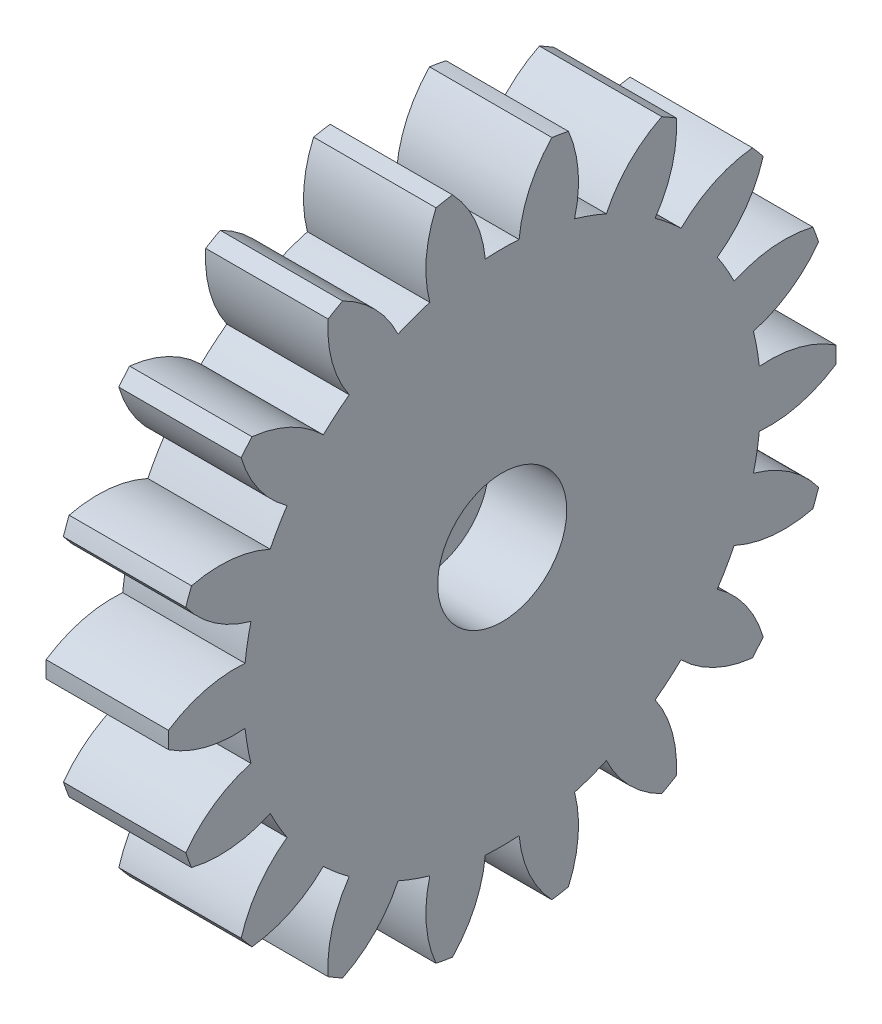
SolidWorks part; units mm, degrees
ref_plane "Plane1" through (0, 0, 0) normal (0, 0, 1) x (1, 0, 0)
ref_plane "Plane2" through (0, 0, 0) normal (0, 1, 0) x (1, 0, 0)
ref_plane "Plane3" through (0, 0, 0) normal (1, 0, 0) x (0, 0, -1)
sketch "HoldingSke" plane through (0, 0, 0) normal (0, 1, 0) x (1, 0, 0)
  line L0 (0, 0) -> (0.634, -0.206)
  line L1 (-15, 0) -> (100, 0) construction
  line L2 (0, 0) -> (-2.1039, 2.3779)
  line L3 (0, 0) -> (-11.863, 4.5341)
  line L4 (0, 0) -> (8.2133, 2.6687)
  line L5 (0, 0) -> (-46.8476, -17.4728)
  line L6 (0, 0) -> (-5.8027, -3.9151)
  line L7 (-2.1039, 2.3779) -> (8.6586, 51.2059)
  line L8 (-76.2, 54.61) -> (-75.3, 54.61)
  line L9 (-71.009, 38.7566) -> (-53.1078, 45.2721)
  line L10 (-76.2, 71.12) -> (104.1128, 71.12)
  line L11 (0, 0) -> (-7, 0)
  line L12 (-76.2, 101.6) -> (-76.147, 101.6)
  line L13 (24.9733, 27.94) -> (52.9518, 28.4284)
  line L14 (24.9733, 27.94) -> (24.9743, 27.94)
  line L15 (24.9733, 27.94) -> (100.4006, 29.5858)
  line L16 (-63.627, -1.5) -> (-12.827, -1.5)
  circle A0 centre (0, 0) radius 2.5
  circle A1 centre (0, 0) radius 11.624
  circle A2 centre (0, 0) radius 37.5
  circle A3 centre (0, 0) radius 2.5
  dimension "MHD" = 23.248
  dimension "Hub_dia" = 75
  dimension "Bore" = 5
  dimension "MBD" = 5
  dimension "Num_teeth" = 18
  dimension "Pitch" = 0.6667
  dimension "Overall_len" = 50
  dimension "Show_teeth" = 18
  dimension "Thickness" = 7
  dimension "OAL" = 50.0001
  dimension "T_dim" = 0.9
  dimension "Ap" = 20
  dimension "H" = 19.05
  dimension "Pitch_radius" = 180.3128
  dimension "Width" = 7
  dimension "Backlash" = 0.053
  dimension "Addendum_fac" = 1
  dimension "Dedendum_fac" = 1.25
  dimension "Clearance_fac" = 0.25
  dimension "Dedendum_add" = 0.001
  dimension "Module" = 1.5
sketch "BasProSke" plane through (0, 0, 0) normal (0, 1, 0) x (1, 0, 0)
  line L0 (-10, 0) -> (60, 0) construction
  line L1 (0, 0) -> (0, 15)
  line L2 (0, 0) -> (7, 0)
  line L3 (7, 0) -> (7, 15)
  line L4 (7, 15) -> (0, 15)
  dimension "Thickness" = 7
  dimension "Diameter" = 30
revolve "Base-Revolve" add sketch "BasProSke" angle 360 about L0
sketch "TooCutSke" plane through (0, 0, 0) normal (1, 0, 0) x (0, 0, -1)
  line L1 (0, 0) -> (0, 107) construction
  line L2 (0, 0) -> (-1.2693, 13.4402) construction
  line L3 (0, 0) -> (-4.6734, 26.504) construction
  line L4 (-1.2693, 13.4402) -> (-2.3367, 13.252) construction
  arc A0 (0.76, 11.5991) -> (-0.76, 11.5991) centre (0, 0) ccw
  arc A1 (2.2542, 14.8553) -> (-2.2542, 14.8553) centre (0, 0) ccw
  circle A2 centre (0, 0) radius 13.5 construction
  circle A3 centre (0, 0) radius 12.6859 construction
  arc A4 (-0.76, 11.5991) -> (-2.2542, 14.8553) centre (-6.1371, 11.1026) ccw
  arc A5 (2.2542, 14.8553) -> (0.76, 11.5991) centre (6.1371, 11.1026) ccw
  dimension "Root_dia" = 23.248
  dimension "Overcut_dia" = 30.0508
  dimension "Pitch_dia" = 27
  dimension "Base_dia" = 25.3717
  dimension "Flank_rad" = 5.4
  dimension "Half_ang" = 10
  dimension "Half_CT" = 1.0839
extrude "ToothCut" cut sketch "TooCutSke" along normal through all
fillet "Breaks" [suppressed] radius 0.03
fillet "RootFillets" [suppressed] radius 0.376
pattern_circular "TeethCuts" count 18 every 20 about axis through (-10, 0, 0) along (1, 0, 0) of "ToothCut", "RootFillets", "Breaks"
sketch "HubNeaOneSke" plane through (0, 0, 0) normal (-1, 0, 0) x (0, 0, 1)
  circle A0 centre (0, 0) radius 11.624
  dimension "Diameter" = 23.248
extrude "HubNearOne" [suppressed] add sketch "HubNeaOneSke" along normal blind 43.0001
sketch "HubNeaBotSke" plane through (0, 0, 0) normal (-1, 0, 0) x (0, 0, 1)
  circle A0 centre (0, 0) radius 11.624
  dimension "Diameter" = 23.248
extrude "HubNearBoth" [suppressed] add sketch "HubNeaBotSke" along normal blind 21.5
ref_plane "FarPln" through (7, 0, 0) normal (1, 0, 0) x (0, 0, -1)
sketch "HubFarSke" plane through (7, 0, 0) normal (1, 0, 0) x (0, 0, -1)
  circle A0 centre (0, 0) radius 11.624
  dimension "Diameter" = 23.248
extrude "HubFar" [suppressed] add sketch "HubFarSke" along normal blind 21.5
sketch "BorSke" plane through (0, 0, 0) normal (1, 0, 0) x (0, 0, -1)
  circle A0 centre (0, 0) radius 2.5
  dimension "Diameter" = 5
extrude "Bore" cut sketch "BorSke" along normal mid plane 100.0001
sketch "KeySke" plane through (0, 0, 0) normal (1, 0, 0) x (0, 0, -1)
  line L0 (-1, 0) -> (-1, 3.4)
  line L1 (-1, 3.4) -> (1, 3.4)
  line L2 (1, 3.4) -> (1, 0)
  line L3 (0, 0) -> (0, 34) construction
  line L4 (-1, 0) -> (1, 0)
  dimension "Offset" = 3.4
  dimension "Width" = 2
extrude "Keyway" [suppressed] cut sketch "KeySke" along normal mid plane 100.0001
pattern_circular "Keyway2" [suppressed] count 2 every 90 about axis through (-10, 0, 0) along (1, 0, 0)
sketch "Croquis1" plane through (7, 0, 0) normal (1, 0, 0) x (0, 0, -1)
  circle A0 centre (0, 0) radius 2.9
  dimension "D1" = 5.8
extrude "Cortar-Extruir1" cut sketch "Croquis1" against normal blind 10
ref_plane "Plano1" through (2, 0, 0) normal (-1, 0, 0) x (0, 0, 1)
sketch "Croquis4" plane through (2, 0, 0) normal (-1, 0, 0) x (0, 0, 1)
  circle A0 centre (0, 0) radius 3.4891
extrude "Saliente-Extruir1" add sketch "Croquis4" along normal through all
sketch "Croquis5" plane through (2, 0, 0) normal (1, 0, 0) x (0, 0, -1)
  circle A0 centre (0, 0) radius 1.9
  dimension "D1" = 3.8
extrude "Cortar-Extruir3" cut sketch "Croquis5" against normal blind 5
sketch "Croquis6" plane through (7, 0, 0) normal (1, 0, 0) x (0, 0, -1)
  circle A0 centre (0, 0) radius 21.9727
extrude "Cortar-Extruir4" cut sketch "Croquis6" against normal blind 1.5
equation "' \"Module@HoldingSke\" = 6.35"
equation "' \"Num_teeth@HoldingSke\" = 12"
equation "' \"Ap@HoldingSke\" =  20"
equation "' \"Ap@HoldingSke\" = 20"
equation "' \"Width@HoldingSke\" = 0.5 * 25.4"
equation "' \"Hub_dia@HoldingSke\"= 1 * 25.4"
equation "' \"Hub_dia@HoldingSke\" = 1 * 25.4"
equation "' \"Overall_len@HoldingSke\" = 1.0 * 25.4"
equation "' \"Bore@HoldingSke\" = 0.75 * 25.4"
equation "' \"T_dim@HoldingSke\" = 0.1 * 25.4"
equation "' \"Width@KeySke\" = 0.25 * 25.4"
equation "' \"Show_teeth@HoldingSke\" = 13"
equation "' \"Backlash@HoldingSke\" = 0.009 * 25.4"
equation "' \"Addendum_fac@HoldingSke\" = 1.0"
equation "' \"Dedendum_fac@HoldingSke\" = 1.25"
equation "' \"Dedendum_add@HoldingSke\" = 0.00005 * 25.4"
equation "' \"Clearance_fac@HoldingSke\" = 0.25"
equation "\"Pitch@HoldingSke\" = 1 / \"Module@HoldingSke\""
equation "\"Overcut_dia@TooCutSke\" = (\"Num_teeth@HoldingSke\" + 2 * \"Addendum_fac@HoldingSke\") / \"Pitch@HoldingSke\" + 0.002 * 25.4"
equation "\"Pitch_dia@TooCutSke\" = \"Num_teeth@HoldingSke\" / \"Pitch@HoldingSke\""
equation "\"Base_dia@TooCutSke\" = \"Num_teeth@HoldingSke\" / \"Pitch@HoldingSke\" * cos((\"Ap@HoldingSke\"  * 3.14159265 / 180))"
equation "\"Root_dia@TooCutSke\" = (\"Num_teeth@HoldingSke\" + 2) / \"Pitch@HoldingSke\" - 2 * (\"Addendum_fac@HoldingSke\" + \"Dedendum_fac@HoldingSke\") / \"Pitch@HoldingSke\" - \"Dedendum_add@HoldingSke\" * 2"
equation "\"Half_ang@TooCutSke\" = 180 / \"Num_teeth@HoldingSke\""
equation "\"Half_CT@TooCutSke\" = \"Num_teeth@HoldingSke\" / \"Pitch@HoldingSke\" * sin((3.14159265 / 2 / \"Num_teeth@HoldingSke\")) / 2 - 7 * \"Backlash@HoldingSke\" / 4"
equation "\"Flank_rad@TooCutSke\" = \"Num_teeth@HoldingSke\" / \"Pitch@HoldingSke\" / 5"
equation "\"Radius@RootFillets\" = \"Clearance_fac@HoldingSke\" / \"Pitch@HoldingSke\" + \"Dedendum_add@HoldingSke\""
equation "\"Break_rad@Breaks\" = 0.02 / \"Pitch@HoldingSke\""
equation "\"Thickness@HoldingSke\" = \"Width@HoldingSke\""
equation "\"OAL@HoldingSke\" = \"Thickness@HoldingSke\""
equation "\"MHD@HoldingSke\" = (\"Num_teeth@HoldingSke\" + 2) / \"Pitch@HoldingSke\" - 2 * (\"Addendum_fac@HoldingSke\" + \"Dedendum_fac@HoldingSke\")  / \"Pitch@HoldingSke\" - \"Dedendum_add@HoldingSke\" * 2"
equation "\"MBD@HoldingSke\" = (\"Num_teeth@HoldingSke\" + 2) / \"Pitch@HoldingSke\" - 2 * (\"Addendum_fac@HoldingSke\" + \"Dedendum_fac@HoldingSke\")  / \"Pitch@HoldingSke\" - \"Dedendum_add@HoldingSke\" * 2 - 0.002 * 25.4"
equation "\"MHD@HoldingSke\" = ((sgn( \"MHD@HoldingSke\" - \"Hub_dia@HoldingSke\" )-1)*( \"MHD@HoldingSke\" - \"Hub_dia@HoldingSke\" ))/-2+ \"Hub_dia@HoldingSke\""
equation "\"MBD@HoldingSke\" = ((sgn( \"MBD@HoldingSke\" - \"Bore@HoldingSke\" )-1)*( \"MBD@HoldingSke\" - \"Bore@HoldingSke\" ))/-2+ \"Bore@HoldingSke\""
equation "\"OAL@HoldingSke\" = ((sgn( \"OAL@HoldingSke\" - \"Overall_len@HoldingSke\" )+1)*( \"OAL@HoldingSke\" - \"Overall_len@HoldingSke\" ))/2 + \"Overall_len@HoldingSke\" + 0.000002 * 25.4"
equation "\"Num_teeth@TeethCuts\" = int( \"Show_teeth@HoldingSke\" ) + 1"
equation "\"Num_teeth@TeethCuts\" = ((sgn( \"Num_teeth@TeethCuts\" - \"Num_teeth@HoldingSke\" )-1)*( \"Num_teeth@TeethCuts\" - \"Num_teeth@HoldingSke\" ))/-2+ \"Num_teeth@HoldingSke\""
equation "\"Num_teeth@TeethCuts\" = ((sgn( \"Num_teeth@TeethCuts\" - 2.0)+1)*( \"Num_teeth@TeethCuts\" - 2.0))/2 +2.0"
equation "\"Angle@TeethCuts\" = 360.0 / \"Num_teeth@HoldingSke\""
equation "\"Diameter@BasProSke\" = (\"Num_teeth@HoldingSke\" + 2 * \"Addendum_fac@HoldingSke\") / \"Pitch@HoldingSke\""
equation "\"Thickness@BasProSke\"  = \"Thickness@HoldingSke\""
equation "' \"Fillet_rad@BasProSke\" =  \"Thickness@HoldingSke\" * 0.05"
equation "' \"Fillet_rad@BasProSke\" = \"Thickness@HoldingSke\" * 0.05"
equation "\"MHD@HoldingSke\" = ((sgn( \"MHD@HoldingSke\" - \"Root_dia@TooCutSke\" )-1)*( \"MHD@HoldingSke\" - \"Root_dia@TooCutSke\" ))/-2+ \"Root_dia@TooCutSke\""
equation "\"Diameter@HubNeaOneSke\" = \"MHD@HoldingSke\""
equation "\"Length@HubNearOne\" = \"OAL@HoldingSke\" - \"Thickness@BasProSke\""
equation "\"Diameter@HubNeaBotSke\" = \"MHD@HoldingSke\""
equation "\"Length@HubNearBoth\" = ( \"OAL@HoldingSke\" - \"Thickness@BasProSke\" ) / 2.0"
equation "\"Thickness@FarPln\" = \"Thickness@BasProSke\""
equation "\"Diameter@HubFarSke\" = \"MHD@HoldingSke\""
equation "\"Length@HubFar\" = ( \"OAL@HoldingSke\" - \"Thickness@BasProSke\" ) / 2.0"
equation "\"Diameter@BorSke\" = \"MBD@HoldingSke\""
equation "\"D1@Bore\" = \"OAL@HoldingSke\" * 2.0"
equation "\"D1@Keyway\" = \"OAL@HoldingSke\" * 2.0"
equation "\"Offset@KeySke\" = \"T_dim@HoldingSke\" + \"MBD@HoldingSke\" / 2.0"
